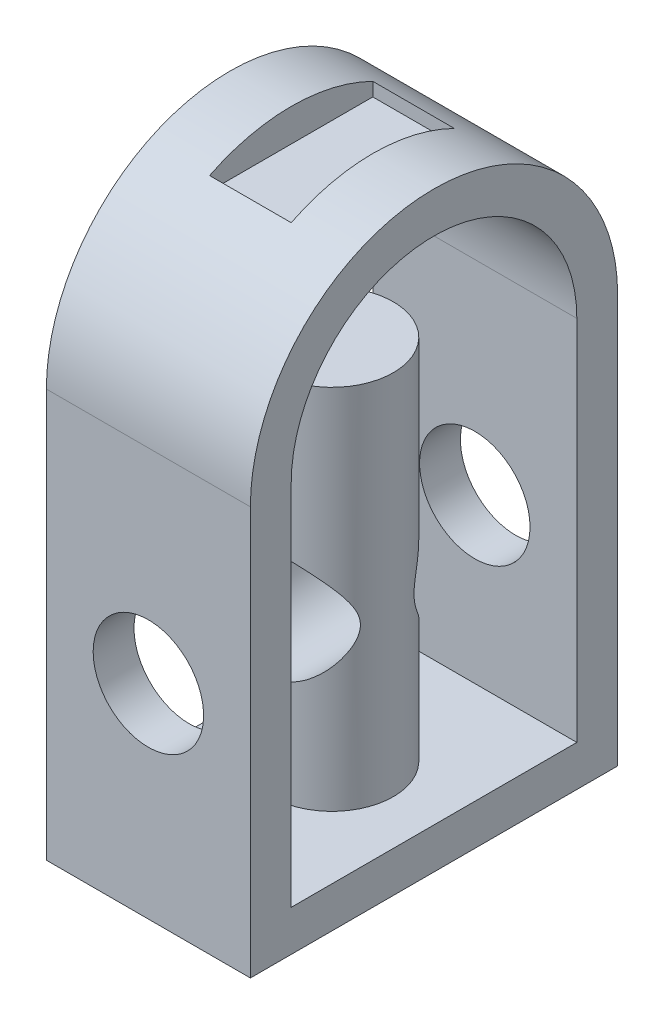
SolidWorks part; units mm, degrees
ref_plane "Front Plane" through (0, 0, 0) normal (0, 0, 1) x (1, 0, 0)
ref_plane "Top Plane" through (0, 0, 0) normal (0, 1, 0) x (1, 0, 0)
ref_plane "Right Plane" through (0, 0, 0) normal (1, 0, 0) x (0, 0, -1)
sketch "Sketch1" plane through (0, 0, 0) normal (1, 0, 0) x (0, 0, -1)
  line L0 (-25.4, -25.4) -> (-25.4, 228.6)
  line L1 (0, 0) -> (177.8, 0)
  line L2 (0, 0) -> (0, 228.6)
  line L3 (0, 228.6) -> (177.8, 228.6) construction
  line L4 (177.8, 0) -> (177.8, 228.6)
  line L5 (203.2, -25.4) -> (203.2, 228.6)
  line L6 (-25.4, -25.4) -> (203.2, -25.4)
  arc A0 (177.8, 228.6) -> (0, 228.6) centre (88.9, 228.6) ccw
  arc A1 (203.2, 228.6) -> (-25.4, 228.6) centre (88.9, 228.6) ccw
  dimension "D1" = 177.8
  dimension "D2" = 228.6
  dimension "D3" = 25.4
extrude "Boss-Extrude2" add sketch "Sketch1" along normal blind 127
ref_plane "Plane1" through (0, 342.9, 0) normal (0, 1, 0) x (1, 0, 0)
sketch "Sketch2" plane through (0, 342.9, 0) normal (0, 1, 0) x (1, 0, 0)
  line L0 (63.5, 139.7) -> (63.5, 203.2) construction
  line L1 (38.1, 139.7) -> (88.9, 139.7)
  line L2 (38.1, 139.7) -> (38.1, 38.1)
  line L3 (38.1, 38.1) -> (88.9, 38.1)
  line L4 (88.9, 139.7) -> (88.9, 38.1)
  line L5 (127, 203.2) -> (0, 203.2) construction
  line L6 (88.9, 88.9) -> (127, 88.9) construction
  line L7 (127, -25.4) -> (127, 203.2) construction
  dimension "D1" = 50.8
  dimension "D2" = 101.6
extrude "Cut-Extrude1" cut sketch "Sketch2" against normal blind 20.32
ref_plane "Plane2" through (0, 2.54, 0) normal (0, 1, 0) x (1, 0, 0)
sketch "Sketch4" plane through (0, 2.54, 0) normal (0, 1, 0) x (1, 0, 0)
  line L0 (63.5, 203.2) -> (63.5, 88.9) construction
  line L1 (127, 203.2) -> (0, 203.2) construction
  line L2 (63.5, 88.9) -> (127, 88.9) construction
  line L3 (127, -25.4) -> (127, 203.2) construction
  circle A0 centre (63.5, 88.9) radius 38.2129
  point P3 (63.5, 88.9)
  point P9 (0, 0)
  point P10 (0, 0)
  point P11 (0, 0)
  point P12 (0, 0)
  point P13 (59.0197, 91.6298)
  point P14 (52.9132, 96.2325)
  point P15 (0, 0)
  point P16 (63.5, 88.9)
extrude "Boss-Extrude3" add sketch "Sketch4" along normal blind 228.6 separate body
ref_plane "Plane3" through (0, 0, -205.74) normal (0, 0, -1) x (-1, 0, 0)
sketch "Sketch5" plane through (0, 0, -205.74) normal (0, 0, -1) x (-1, 0, 0)
  line L0 (-63.5, 228.6) -> (-63.5, 101.6) construction
  line L1 (-127, 228.6) -> (0, 228.6) construction
  line L2 (-63.5, 101.6) -> (0, 101.6) construction
  line L3 (0, -25.4) -> (0, 228.6) construction
  circle A0 centre (-63.5, 101.6) radius 34.3797
  point P3 (-63.5, 101.6)
extrude "Cut-Extrude2" cut sketch "Sketch5" against normal through all
